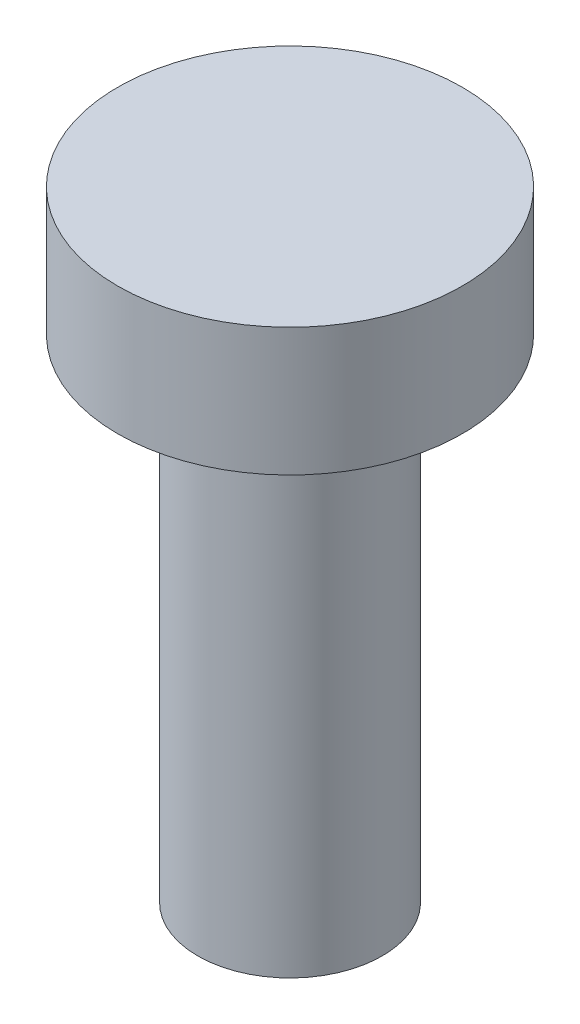
SolidWorks part; units mm, degrees
material "A-1"
ref_plane "Front Plane" through (0, 0, 0) normal (0, 0, 1) x (1, 0, 0)
ref_plane "Top Plane" through (0, 0, 0) normal (0, 1, 0) x (1, 0, 0)
ref_plane "Right Plane" through (0, 0, 0) normal (1, 0, 0) x (0, 0, -1)
sketch "Sketch1" plane through (0, 0, 0) normal (0, 0, 1) x (1, 0, 0)
  line L1 (2.3812, 12.7) -> (4.445, 12.7)
  line L2 (0, 12.7) -> (0, 0) construction
  line L3 (0, 0) -> (2.3813, 0)
  line L4 (2.3812, 12.7) -> (2.3813, 0)
  line L5 (55, 0) -> (-55, 0) construction
  line L6 (4.445, 12.7) -> (4.445, 16.002)
  line L7 (4.445, 16.002) -> (0, 16.002)
  line L8 (0, 0) -> (0, 16.002)
  point P4 (3.4131, 12.7)
  dimension "D1" = 12.7
  dimension "D2" = 4.7625
  dimension "D3" = 8.89
  dimension "D4" = 3.302
revolve "Revolve1" add sketch "Sketch1" angle 360 about L2
